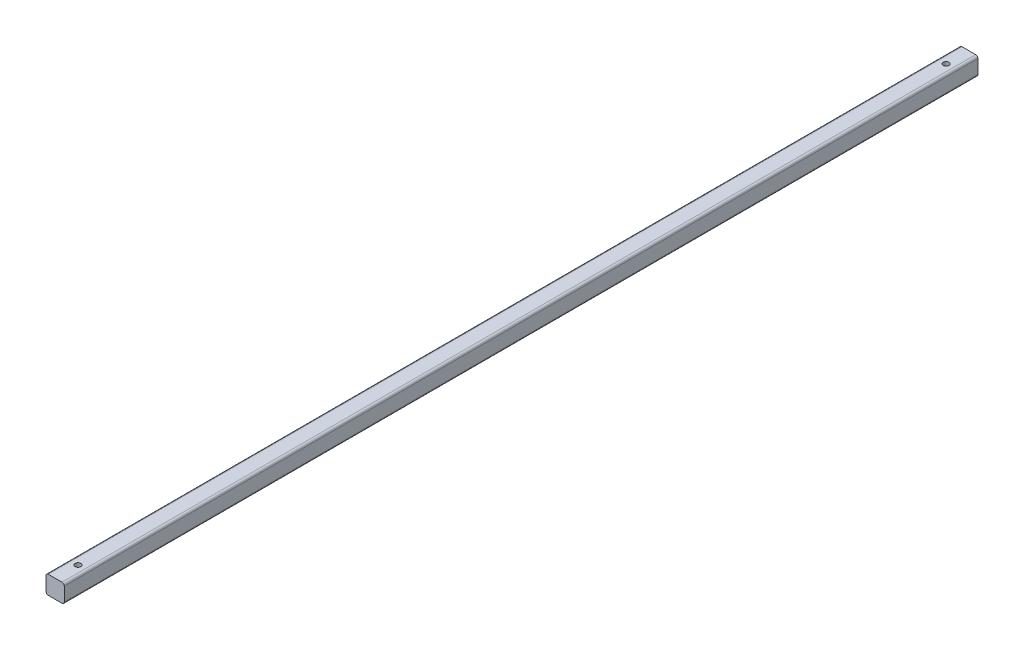
SolidWorks part; units mm, degrees
material "AISI 304"
ref_plane "Front Plane" through (0, 0, 0) normal (0, 0, 1) x (1, 0, 0)
ref_plane "Top Plane" through (0, 0, 0) normal (0, 1, 0) x (1, 0, 0)
ref_plane "Right Plane" through (0, 0, 0) normal (1, 0, 0) x (0, 0, -1)
sketch "Sketch1" plane through (0, 0, 0) normal (0, 0, 1) x (1, 0, 0)
  line L1 (2, -2) -> (-2, -2)
  line L2 (2, -2) -> (2, 2)
  line L3 (2, 2) -> (-2, 2)
  line L4 (-2, -2) -> (-2, 2)
  line L5 (2, -2) -> (-2, 2) construction
  line L6 (2, 2) -> (-2, -2) construction
  point P0 (0, 0)
extrude "Boss-Extrude1" add sketch "Sketch1" along normal mid plane 200
fillet "Fillet1" radius 0.5
sketch "Sketch2" plane through (0, 2, 0) normal (0, 1, 0) x (1, 0, 0)
  line L0 (-2, 0) -> (2, 0) construction
  line L1 (-2, -100) -> (-2, 100) construction
  line L2 (2, 100) -> (2, -100) construction
  line L3 (1.5, 100) -> (-1.5, 100) construction
  point P0 (0, -95)
  point P1 (0, 95)
  dimension "D1" = 5
hole_wizard "Tap Drill for M1.6 Tap1" positions "3DSketch1" profile "Sketch3" hole size "M1.6" standard "GB" end condition through all
sketch3d "3DSketch1"
  point P0 (0, 2, -95)
  point P3 (0, 2, 95)
sketch "Sketch3" plane through (0, 2, -95) normal (1, 0, 0) x (0, 0, 1)
  line L0 (0, 0) -> (0, 4)
  line L1 (0, 4) -> (0.625, 4)
  line L2 (0.625, 4) -> (0.625, 0)
  line L5 (0.625, 0) -> (0, 0)
  line L11 (0, -6.35) -> (0, 107.95) construction
  dimension "Thru Hole Dia." = 1.25
  dimension "Thru Hole Depth" = 4
